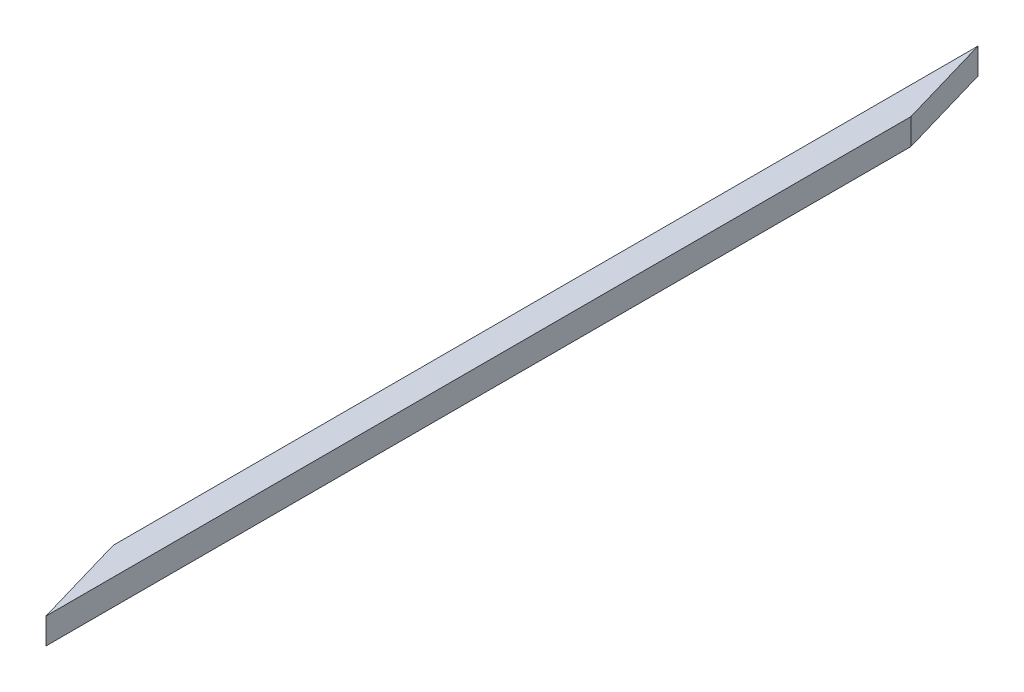
SolidWorks part; units mm, degrees
ref_plane "Front Plane" through (0, 0, 0) normal (0, 0, 1) x (1, 0, 0)
ref_plane "Top Plane" through (0, 0, 0) normal (0, 1, 0) x (1, 0, 0)
ref_plane "Right Plane" through (0, 0, 0) normal (1, 0, 0) x (0, 0, -1)
sketch "Sketch1" plane through (0, 0, 0) normal (0, 0, 1) x (1, 0, 0)
  line L1 (-32.0225, 27.5281) -> (17.9775, 27.5281)
  line L2 (-32.0225, 27.5281) -> (-32.0225, -19.4719)
  line L3 (-32.0225, -19.4719) -> (17.9775, -19.4719)
  line L4 (17.9775, 27.5281) -> (17.9775, -19.4719)
  dimension "D1" = 50
  dimension "D2" = 47
extrude "Boss-Extrude1" add sketch "Sketch1" along normal blind 1737.37
sketch "Sketch2" plane through (0, 27.5281, 0) normal (0, 1, 0) x (1, 0, 0)
  line L0 (-32.0225, 0) -> (17.9775, 0)
  line L9 (17.9775, 0) -> (-32.0225, 0)
  line L10 (17.9775, -171.6104) -> (17.9775, 0)
  line L11 (17.9775, -1737.37) -> (17.9775, 0) construction
  line L12 (438.4777, -1614.8541) -> (-32.0225, 0) construction
  line L13 (-32.0225, 0) -> (17.9775, -171.6104)
  line L14 (17.9775, 0) -> (17.9775, -171.6104)
  line L15 (17.9775, -1737.37) -> (-32.0225, -1737.37)
  line L16 (-32.0225, -1737.37) -> (-32.0225, -1565.8147)
  line L17 (-32.0225, -1737.37) -> (-32.0225, 0) construction
  line L18 (17.9628, -1737.3743) -> (-452.5374, -122.5202) construction
  line L19 (-32.0225, -1565.8147) -> (17.9775, -1737.37)
  line M4 (17.9775, 0) -> (-32.0225, 0)
  line M5 (-32.0225, 0) -> (-32.0225, -1737.37)
  line M6 (-32.0225, -1737.37) -> (17.9775, -1737.37)
  line M7 (17.9775, -1737.37) -> (17.9775, 0)
extrude "Cut-Extrude1" cut sketch "Sketch2" against normal blind 50 contours L13 M4 M7 | L19 M5 M6
